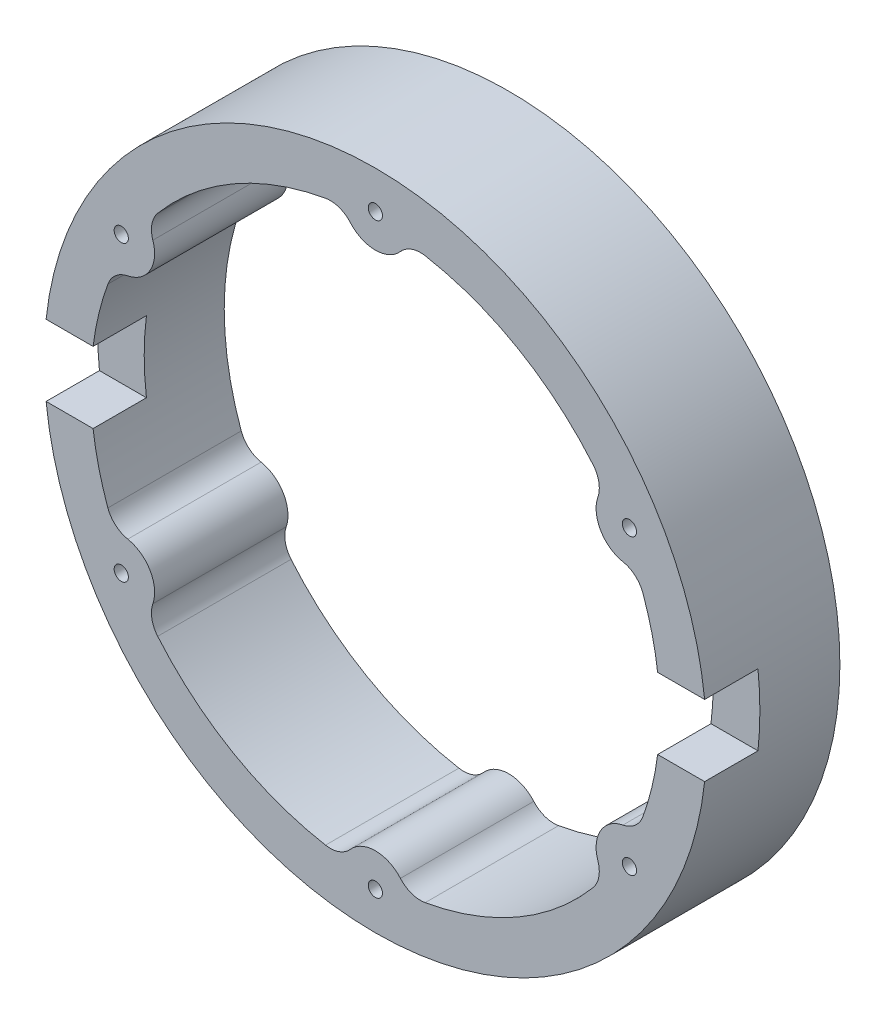
SolidWorks part; units mm, degrees
material "Hêtre"
ref_plane "Plan de face" through (0, 0, 0) normal (0, 0, 1) x (1, 0, 0)
ref_plane "Plan de dessus" through (0, 0, 0) normal (0, 1, 0) x (1, 0, 0)
ref_plane "Plan de droite" through (0, 0, 0) normal (1, 0, 0) x (0, 0, -1)
sketch "Esquisse1" plane through (0, 0, 0) normal (0, 0, 1) x (1, 0, 0)
  circle A0 centre (0, 0) radius 74.5
  dimension "D1" = 149
extrude "Boss.-Extru.1" add sketch "Esquisse1" along normal blind 30
sketch "Esquisse3" plane through (0, 0, 0) normal (0, 0, -1) x (-1, 0, 0)
  circle A0 centre (0, 0) radius 64
  dimension "D1" = 128
extrude "Enlèv. mat.-Extru.1" cut sketch "Esquisse3" against normal through all
sketch "Esquisse4" plane through (0, 0, 0) normal (0, 0, -1) x (-1, 0, 0)
  line L0 (0, 0) -> (0, 71.3152) construction
  arc A0 (-11.205, 63.0115) -> (-5.6414, 61.0579) centre (-10.1545, 57.1042) cw
  circle A1 centre (0, 0) radius 64 construction
  arc A2 (-5.6414, 61.0579) -> (0, 58.5) centre (0, 66) ccw
  arc A3 (-11.205, 63.0115) -> (11.205, 63.0115) centre (0, 0) cw
  arc A4 (11.205, 63.0115) -> (5.6414, 61.0579) centre (10.1545, 57.1042) ccw
  arc A5 (5.6414, 61.0579) -> (0, 58.5) centre (0, 66) cw
  dimension "D1" = 7.5
  dimension "D2" = 6
  dimension "D3" = 66
  dimension "D4" = 58
  dimension "D5" = 10.1545
extrude "Boss.-Extru.2" add sketch "Esquisse4" against normal up to surface (30 mm away) up to face at (-64, 0, 30)
sketch "Esquisse5" plane through (0, 0, 0) normal (0, 0, -1) x (-1, 0, 0)
  circle A0 centre (0, 66) radius 1.6
  arc A1 (-5.6414, 61.0579) -> (5.6414, 61.0579) centre (0, 66) ccw construction
  dimension "D1" = 3.2
extrude "Enlèv. mat.-Extru.2" cut sketch "Esquisse5" against normal blind 120
pattern_circular "Répétition circulaire1" count 6 over 360 about axis through (0, 0, 0) along (0, 0, 1) of "Enlèv. mat.-Extru.2", "Boss.-Extru.2"
sketch "Esquisse7" plane through (0, 0, 0) normal (1, 0, 0) x (0, 0, -1)
  line L0 (-30, -8) -> (-30, 8)
  line L1 (-30, 8) -> (-18, 8)
  line L2 (-18, 8) -> (-18, -8)
  line L3 (-18, -8) -> (-30, -8)
  line L4 (-30, 21.8019) -> (-30, -21.8019) construction
  line L5 (0, 0) -> (-34.8639, 0) construction
  dimension "D1" = 16
  dimension "D2" = 12
extrude "Enlèv. mat.-Extru.3" cut sketch "Esquisse7" against normal through all both and the other way through all
